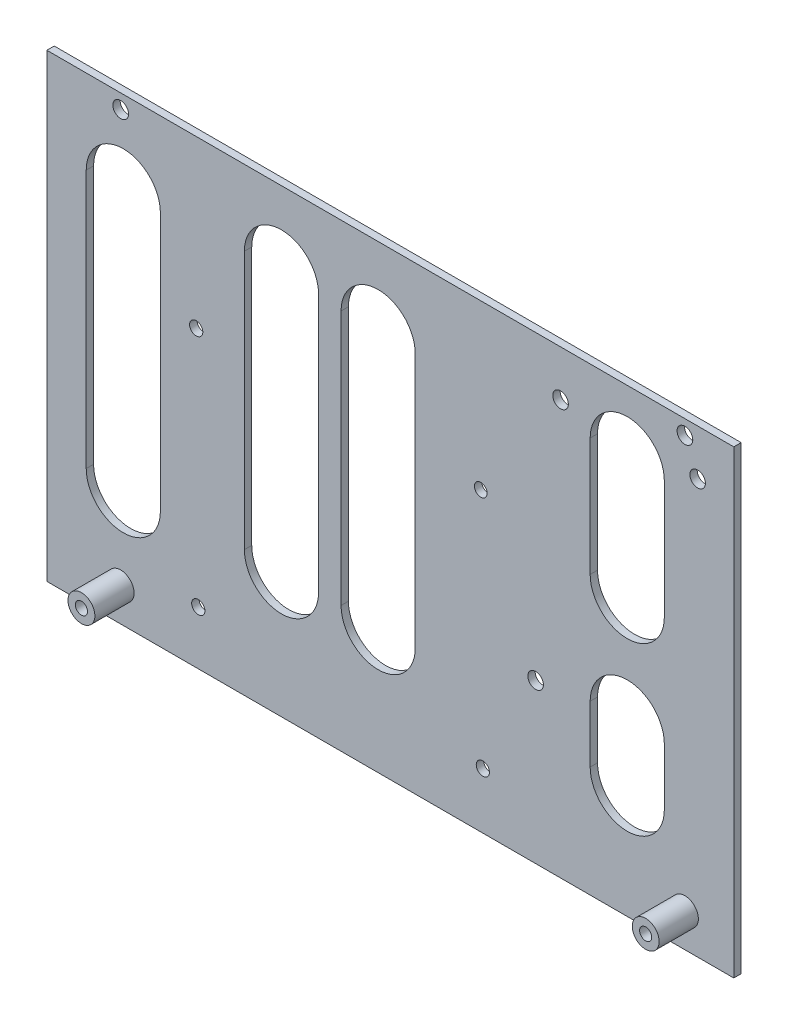
SolidWorks part; units mm, degrees
ref_plane "Front Plane" through (0, 0, 0) normal (0, 0, 1) x (1, 0, 0)
ref_plane "Top Plane" through (0, 0, 0) normal (0, 1, 0) x (1, 0, 0)
ref_plane "Right Plane" through (0, 0, 0) normal (1, 0, 0) x (0, 0, -1)
sketch "Sketch1" plane through (0, 0, 0) normal (0, 0, 1) x (1, 0, 0)
  line L0 (32, 242.9727) -> (172, 242.9727)
  line L1 (32, 242.9727) -> (32, 149.2189)
  line L2 (172, 242.9727) -> (172, 149.2189)
  line L3 (32, 149.2189) -> (172, 149.2189)
  line L4 (29, 242.9727) -> (174.2, 242.9727) construction
  line L5 (29, 242.9727) -> (29, 240.0279) construction
  dimension "D1" = 140
  dimension "D2" = 3
extrude "Boss-Extrude1" add sketch "Sketch1" along normal blind 1.5
sketch "Sketch2" plane through (0, 0, 1.5) normal (0, 0, 1) x (1, 0, 0)
  circle A0 centre (47.044, 240.0279) radius 1.6
  circle A1 centre (162.044, 240.0279) radius 1.6
extrude "Cut-Extrude1" cut sketch "Sketch2" against normal blind 1.5
sketch "Sketch3" plane through (0, 0, 1.5) normal (0, 0, 1) x (1, 0, 0)
  circle A0 centre (47.044, 156.0279) radius 1.2376
  circle A1 centre (162.044, 156.0279) radius 1.2376
  circle A2 centre (47.044, 156.0279) radius 2.7376
  circle A3 centre (162.044, 156.0279) radius 2.7376
  dimension "D1" = 1.5
extrude "Boss-Extrude2" add sketch "Sketch3" along normal blind 8
sketch "Sketch4" plane through (0, 0, 0) normal (0, 0, -1) x (-1, 0, 0)
  circle A0 centre (-120.4318, 209.6172) radius 1.3
  circle A1 centre (-62.434, 209.1111) radius 1.35
  circle A2 centre (-62.8616, 160.1129) radius 1.35
  circle A3 centre (-120.8594, 160.6191) radius 1.35
  circle A4 centre (-131.6131, 181.5519) radius 1.5875
  circle A5 centre (-136.6931, 233.6219) radius 1.5875
  circle A6 centre (-164.6331, 233.6219) radius 1.5875
extrude "Cut-Extrude2" cut sketch "Sketch4" against normal blind 8
sketch "Sketch5" plane through (0, 0, 1.5) normal (0, 0, 1) x (1, 0, 0)
  line L0 (79.8137, 227.627) -> (79.8137, 174.9535) construction
  line L1 (87.37, 227.627) -> (87.37, 174.9535)
  line L2 (72.2574, 227.627) -> (72.2574, 174.9535)
  line L3 (99.5204, 226.9356) -> (99.5204, 174.9535) construction
  line L4 (107.0767, 226.9356) -> (107.0767, 174.9535)
  line L5 (91.964, 226.9356) -> (91.964, 174.9535)
  line L6 (150.2878, 205.8186) -> (150.2878, 229.8973) construction
  line L7 (142.7315, 205.8186) -> (142.7315, 229.8973)
  line L8 (157.8442, 205.8186) -> (157.8442, 229.8973)
  line L9 (150.2878, 183.4365) -> (150.2878, 171.8213) construction
  line L10 (157.8442, 183.4365) -> (157.8442, 171.8213)
  line L11 (142.7315, 183.4365) -> (142.7315, 171.8213)
  line L12 (47.5783, 225.8257) -> (47.5783, 173.1522) construction
  line L13 (55.1346, 225.8257) -> (55.1346, 173.1522)
  line L14 (40.022, 225.8257) -> (40.022, 173.1522)
  arc A0 (87.37, 227.627) -> (72.2574, 227.627) centre (79.8137, 227.627) ccw
  arc A1 (72.2574, 174.9535) -> (87.37, 174.9535) centre (79.8137, 174.9535) ccw
  arc A2 (107.0767, 226.9356) -> (91.964, 226.9356) centre (99.5204, 226.9356) ccw
  arc A3 (91.964, 174.9535) -> (107.0767, 174.9535) centre (99.5204, 174.9535) ccw
  arc A4 (142.7315, 205.8186) -> (157.8442, 205.8186) centre (150.2878, 205.8186) ccw
  arc A5 (157.8442, 229.8973) -> (142.7315, 229.8973) centre (150.2878, 229.8973) ccw
  arc A6 (157.8442, 183.4365) -> (142.7315, 183.4365) centre (150.2878, 183.4365) ccw
  arc A7 (142.7315, 171.8213) -> (157.8442, 171.8213) centre (150.2878, 171.8213) ccw
  arc A8 (55.1346, 225.8257) -> (40.022, 225.8257) centre (47.5783, 225.8257) ccw
  arc A9 (40.022, 173.1522) -> (55.1346, 173.1522) centre (47.5783, 173.1522) ccw
  point P2 (79.8137, 201.2903)
  point P7 (99.5204, 200.9446)
  point P14 (150.2878, 217.8579)
  point P21 (150.2878, 177.6289)
  point P28 (150.4184, 171.8213)
  point P29 (150.2878, 183.4365)
  point P32 (47.5783, 199.489)
extrude "Cut-Extrude3" cut sketch "Sketch5" against normal blind 10
